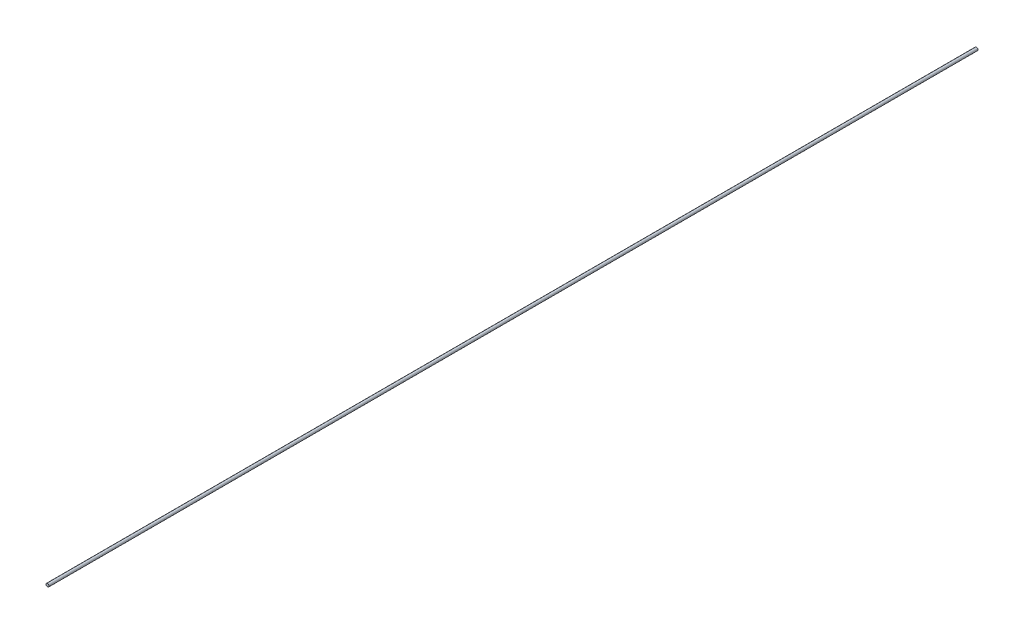
SolidWorks part; units mm, degrees
material "Hexcel AS4C (3000 Filaments)"
ref_plane "Front Plane" through (0, 0, 0) normal (0, 0, 1) x (1, 0, 0)
ref_plane "Top Plane" through (0, 0, 0) normal (0, 1, 0) x (1, 0, 0)
ref_plane "Right Plane" through (0, 0, 0) normal (1, 0, 0) x (0, 0, -1)
sketch "Sketch1" plane through (0, 0, 0) normal (0, 0, 1) x (1, 0, 0)
  circle A0 centre (0, 0) radius 1
  dimension "D1" = 2
extrude "Boss-Extrude1" add sketch "Sketch1" along normal blind 610
